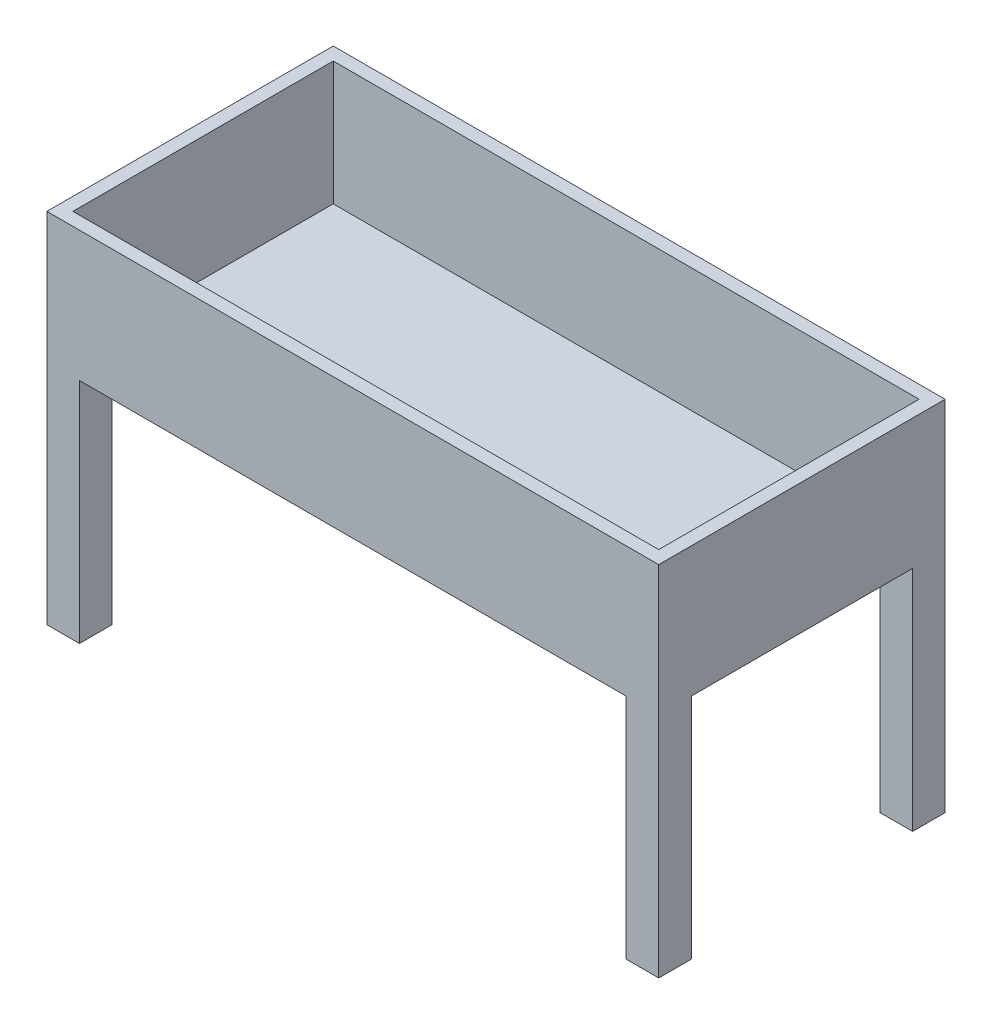
SolidWorks part; units mm, degrees
ref_plane "前视基准面" through (0, 0, 0) normal (0, 0, 1) x (1, 0, 0)
ref_plane "上视基准面" through (0, 0, 0) normal (0, 1, 0) x (1, 0, 0)
ref_plane "右视基准面" through (0, 0, 0) normal (1, 0, 0) x (0, 0, -1)
other "Configuration Table"
sketch "草图1" plane through (0, 0, 0) normal (0, 1, 0) x (1, 0, 0)
  line L1 (0, 0) -> (94, 0)
  line L2 (0, 0) -> (0, 44)
  line L3 (0, 44) -> (94, 44)
  line L4 (94, 0) -> (94, 44)
  dimension "D1" = 94
  dimension "D2" = 44
extrude "凸台-拉伸2" add sketch "草图1" along normal blind 20 contours L3 L4 L1 L2
sketch "草图2" plane through (0, 20, 0) normal (0, 1, 0) x (1, 0, 0)
  line L4 (2, 42) -> (92, 42)
  line L5 (2, 42) -> (2, 2)
  line L6 (2, 2) -> (92, 2)
  line L7 (92, 42) -> (92, 2)
  dimension "D3" = 90
  dimension "D4" = 40
extrude "切除-拉伸1" cut sketch "草图2" against normal blind 19
sketch "草图3" plane through (0, 0, 0) normal (0, -1, 0) x (1, 0, 0)
  line L1 (0, 0) -> (5, 0)
  line L2 (0, 0) -> (0, -5)
  line L3 (0, -5) -> (5, -5)
  line L4 (5, 0) -> (5, -5)
  line L10 (89, 0) -> (89, -5)
  line L11 (94, -5) -> (89, -5)
  line L12 (94, 0) -> (94, -5)
  line L13 (94, 0) -> (89, 0)
  line L14 (94, -44) -> (89, -44)
  line L15 (94, -44) -> (94, -39)
  line L16 (94, -39) -> (89, -39)
  line L17 (89, -44) -> (89, -39)
  line L18 (5, -44) -> (5, -39)
  line L19 (0, -39) -> (5, -39)
  line L20 (0, -44) -> (0, -39)
  line L21 (0, -44) -> (5, -44)
  point P5 (0, 0)
  point P6 (0, 0)
  dimension "D1" = 5
  dimension "D2" = 5
extrude "凸台-拉伸3" add sketch "草图3" along normal blind 35
